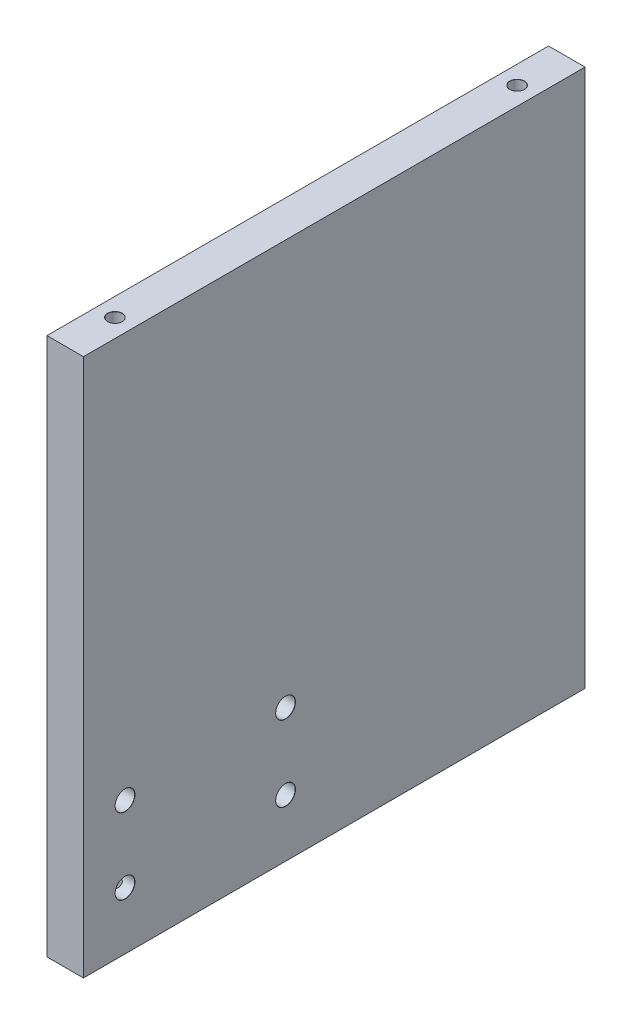
SolidWorks part; units mm, degrees
ref_plane "Front Plane" through (0, 0, 0) normal (0, 0, 1) x (1, 0, 0)
ref_plane "Top Plane" through (0, 0, 0) normal (0, 1, 0) x (1, 0, 0)
ref_plane "Right Plane" through (0, 0, 0) normal (1, 0, 0) x (0, 0, -1)
sketch "Sketch1" plane through (0, 0, 0) normal (1, 0, 0) x (0, 0, -1)
  line L1 (-43.65, -46.825) -> (43.65, -46.825)
  line L2 (-43.65, -46.825) -> (-43.65, 46.825)
  line L3 (-43.65, 46.825) -> (43.65, 46.825)
  line L4 (43.65, -46.825) -> (43.65, 46.825)
  line L5 (-43.65, -46.825) -> (43.65, 46.825) construction
  line L6 (-43.65, 46.825) -> (43.65, -46.825) construction
  point P0 (0, 0)
extrude "Boss-Extrude1" add sketch "Sketch1" along normal blind 6.35
sketch "Sketch2" plane through (0, 46.825, 0) normal (0, 1, 0) x (1, 0, 0)
  line L0 (3.175, 43.65) -> (3.175, 35)
  line L1 (6.35, 43.65) -> (0, 43.65) construction
  line L2 (3.175, -43.65) -> (3.175, -35)
  line L3 (6.35, -43.65) -> (0, -43.65) construction
hole_wizard "Tap Drill for M3x0.5 Tap1" positions "Sketch3" profile "Sketch4" hole size "M3x0.5" standard "ANSI Metric"
sketch "Sketch3" plane through (0, 46.825, 0) normal (0, 1, 0) x (1, 0, 0)
  point P0 (3.175, 35)
  point P3 (3.175, -35)
sketch "Sketch4" plane through (3.175, 46.825, -35) normal (1, 0, 0) x (0, 0, 1)
  line L0 (0, 0) -> (0, 10.7511)
  line L1 (0, 10.7511) -> (1.25, 10)
  line L2 (1.25, 10) -> (1.25, 0.025)
  line L3 (1.25, 0.025) -> (1.275, 0)
  line L5 (1.275, 0) -> (0, 0)
  line L6 (-1.25, 0.025) -> (-1.275, 0) construction
  line L10 (0, 10.7511) -> (-1.25, 10) construction
  line L11 (0, -6.35) -> (0, 107.95) construction
  dimension "Hole Dia." = 2.5
  dimension "Hole Depth" = 10
  dimension "Near C'Sink Dia." = 2.55
  dimension "Near C'Sink Angle" = 90
  dimension "Drill Angle" = 118
sketch "Sketch5" plane through (0, -46.825, 0) normal (0, -1, 0) x (1, 0, 0)
  line L0 (3.175, 43.65) -> (3.175, 35)
  line L1 (3.175, -43.65) -> (3.175, -35)
  line L2 (6.35, -43.65) -> (0, -43.65) construction
hole_wizard "Tap Drill for M3x0.5 Tap2" positions "Sketch6" profile "Sketch7" hole size "M3x0.5" standard "ANSI Metric"
sketch "Sketch6" plane through (0, -46.825, 0) normal (0, -1, 0) x (-1, 0, 0)
  point P0 (-3.175, -35)
  point P3 (-3.175, 35)
sketch "Sketch7" plane through (3.175, -46.825, 35) normal (1, 0, 0) x (0, 0, -1)
  line L0 (0, 0) -> (0, 10)
  line L1 (0, 10) -> (1.25, 9.2489)
  line L2 (1.25, 9.2489) -> (1.25, 0.025)
  line L3 (1.25, 0.025) -> (1.275, 0)
  line L5 (1.275, 0) -> (0, 0)
  line L6 (-1.25, 0.025) -> (-1.275, 0) construction
  line L10 (0, 10) -> (-1.25, 9.2489) construction
  line L11 (0, -6.35) -> (0, 107.95) construction
  dimension "Hole Dia." = 2.5
  dimension "Hole Depth" = 10
  dimension "Near C'Sink Dia." = 2.55
  dimension "Near C'Sink Angle" = 90
  dimension "Drill Angle" = 118
sketch "Sketch8" plane through (6.35, 0, 0) normal (1, 0, 0) x (0, 0, -1)
  line L0 (-43.65, -46.825) -> (-43.65, -36.825)
  line L1 (-43.65, 46.825) -> (-43.65, -46.825) construction
  line L2 (-43.65, -36.825) -> (-36.41, -36.825)
  line L3 (-36.41, -36.825) -> (-8.47, -36.825)
  line L4 (-36.41, -36.825) -> (-36.41, -23.655)
  line L5 (-8.47, -36.825) -> (-8.47, -23.655)
hole_wizard "M3 Clearance Hole1" positions "Sketch9" profile "Sketch10" hole size "M3" standard "ANSI Metric" end condition through all
sketch "Sketch9" plane through (6.35, 0, 0) normal (1, 0, 0) x (0, 0, -1)
  point P0 (-36.41, -23.655)
  point P3 (-8.47, -23.655)
  point P6 (-8.47, -36.825)
  point P9 (-36.41, -36.825)
sketch "Sketch10" plane through (6.35, -23.655, 36.41) normal (0, 1, 0) x (0, 0, -1)
  line L0 (0, 0) -> (0, 6.35)
  line L1 (0, 6.35) -> (1.7, 6.35)
  line L2 (1.7, 6.35) -> (1.7, 0.025)
  line L3 (1.7, 0.025) -> (1.725, 0)
  line L5 (1.725, 0) -> (0, 0)
  line L6 (-1.7, 0.025) -> (-1.725, 0) construction
  line L11 (0, -6.35) -> (0, 107.95) construction
  dimension "Thru Hole Dia." = 3.4
  dimension "Thru Hole Depth" = 6.35
  dimension "Near C'Sink Dia." = 3.45
  dimension "Near C'Sink Angle" = 90
